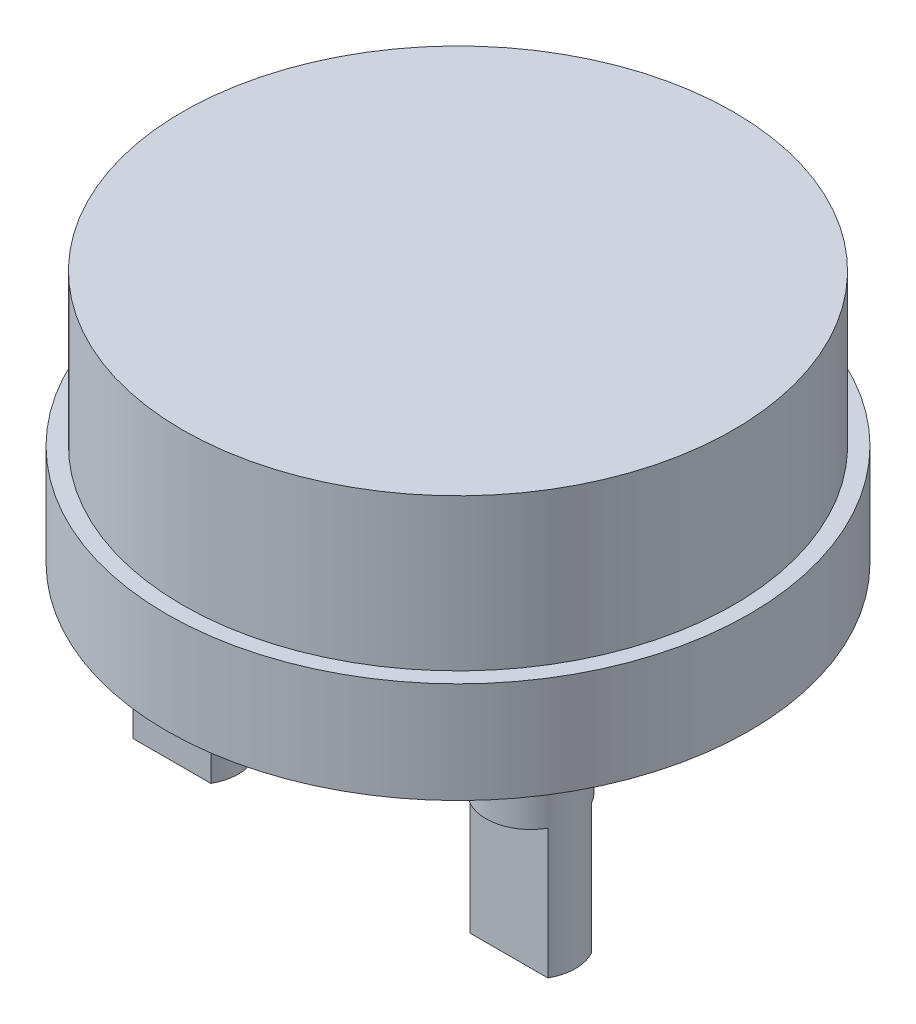
SolidWorks part; units mm, degrees
ref_plane "前视基准面" through (0, 0, 0) normal (0, 0, 1) x (1, 0, 0)
ref_plane "上视基准面" through (0, 0, 0) normal (0, 1, 0) x (1, 0, 0)
ref_plane "右视基准面" through (0, 0, 0) normal (1, 0, 0) x (0, 0, -1)
sketch "草图1" plane through (0, 0, 0) normal (0, 1, 0) x (1, 0, 0)
  circle A0 centre (0, 0) radius 16.35
  dimension "D1" = 32.7
extrude "凸台-拉伸1" add sketch "草图1" along normal blind 9
sketch "草图2" plane through (0, 0, 0) normal (0, -1, 0) x (1, 0, 0)
  circle A0 centre (0, 0) radius 17.29
  dimension "D1" = 34.58
extrude "凸台-拉伸2" add sketch "草图2" along normal blind 6
sketch "草图3" plane through (0, -6, 0) normal (0, -1, 0) x (1, 0, 0)
  line L0 (0, 0) -> (13.2137, 0) construction
  line L1 (0, 0) -> (0, 9.1274) construction
  circle A0 centre (0, 0) radius 5.5
  circle A1 centre (0, 0) radius 5 construction
  circle A2 centre (-6.6, -9.56) radius 1.9
  circle A3 centre (-6.6, -9.56) radius 1.76 construction
  circle A4 centre (-10, 5.68) radius 2.65
  circle A5 centre (-10, 5.68) radius 2.5 construction
  circle A6 centre (6.6, -9.56) radius 1.76 construction
  circle A7 centre (6.6, -9.56) radius 1.9
  circle A8 centre (10, 5.68) radius 2.5 construction
  circle A9 centre (10, 5.68) radius 2.65
  point P16 (0, 6.8864)
  dimension "D1" = 11
  dimension "D2" = 10
  dimension "D3" = 3.8
  dimension "D4" = 3.52
  dimension "D5" = 5
  dimension "D6" = 5.3
  dimension "D7" = 5.68
  dimension "D8" = 10
  dimension "D9" = 9.56
  dimension "D10" = 6.6
extrude "凸台-拉伸3" add sketch "草图3" along normal blind 4
sketch "草图4" plane through (0, -10, 0) normal (0, -1, 0) x (1, 0, 0)
  line L0 (-12.3092, 6.98) -> (-7.6908, 6.98)
  line L1 (-12.3092, 4.38) -> (-7.6908, 4.38)
  line L2 (-10, 6.98) -> (-10, 4.38) construction
  line L3 (0, 0) -> (0, 12.409) construction
  line L4 (12.3092, 6.98) -> (7.6908, 6.98)
  line L5 (12.3092, 4.38) -> (7.6908, 4.38)
  circle A0 centre (-10, 5.68) radius 2.65 construction
  arc A1 (-12.3092, 6.98) -> (-12.3092, 4.38) centre (-10, 5.68) ccw
  arc A4 (-7.6908, 4.38) -> (-7.6908, 6.98) centre (-10, 5.68) ccw
  arc A5 (12.3092, 6.98) -> (12.3092, 4.38) centre (10, 5.68) cw
  arc A6 (7.6908, 4.38) -> (7.6908, 6.98) centre (10, 5.68) cw
  point P13 (-10, 5.68)
  dimension "D1" = 2.6
extrude "凸台-拉伸4" add sketch "草图4" along normal blind 7.7
